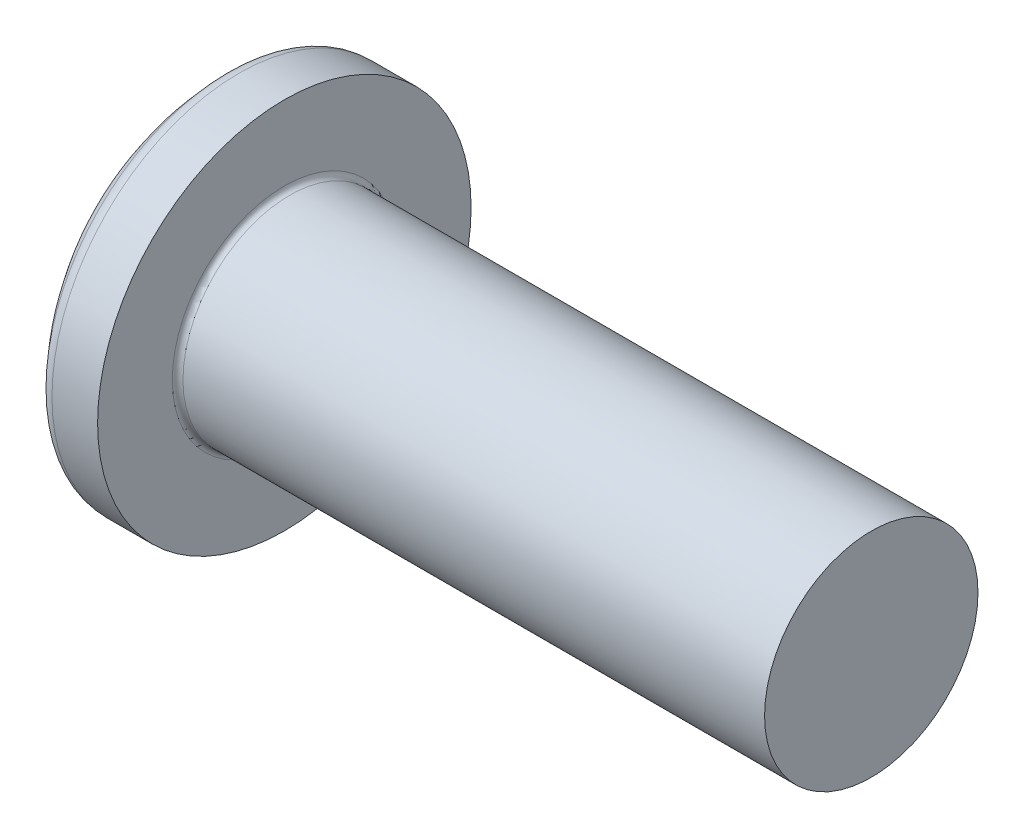
SolidWorks part; units mm, degrees
ref_plane "Plane1" through (0, 0, 0) normal (0, 0, 1) x (1, 0, 0)
ref_plane "Plane2" through (0, 0, 0) normal (0, 1, 0) x (1, 0, 0)
ref_plane "Plane3" through (0, 0, 0) normal (1, 0, 0) x (0, 0, -1)
sketch "BodySke" plane through (0, 0, 0) normal (0, 0, 1) x (1, 0, 0)
  line L0 (2.4, 2) -> (2.4, 3.5)
  line L1 (2.65, 6.35) -> (2.65, -3.175) construction
  line L2 (-25.4, 0) -> (127, 0) construction
  line L3 (13.4, 0) -> (0, 0)
  line L4 (2.4, 2) -> (13.4, 2)
  line L5 (13.4, 2) -> (13.4, 0)
  line L6 (1.5446, 3.5) -> (2.4, 3.5)
  line L8 (7.4, 6.35) -> (7.4, -3.175) construction
  arc A0 (1.3473, 3.4144) -> (0, 0) centre (5, 0) ccw
  arc A2 (1.3473, 3.4144) -> (1.5446, 3.5) centre (1.5446, 3.23) cw
  dimension "Head_crown_rad" = 5
  dimension "Head_fillet_rad" = 0.27
  dimension "Length" = 11
  dimension "Head_ht" = 2.4
  dimension "Head_dia" = 7
  dimension "Advance" = 0.5
  dimension "Thread_nom" = 6
  dimension "Diameter" = 4
revolve "Base-Revolve" add sketch "BodySke"
cosmetic thread "ThreadCosmetic" [suppressed]
fillet "Fillet1" radius 0.1 1 edges at (2.4, 0, 2)
sketch "Sketch3" plane through (0, 0, 0) normal (1, 0, 0) x (0, 0, -1)
  line L0 (0.37, -1.4) -> (-0.37, -1.4)
  line L1 (0.37, -1.4) -> (0.37, 1.4)
  line L2 (-0.37, 1.4) -> (0.37, 1.4)
  line L3 (-0.37, 1.4) -> (-0.37, -1.4)
  dimension "Cross_dia" = 2.8
  dimension "D1" = 1.4
  dimension "Cross_width" = 0.74
  dimension "D2" = 0.37
ref_plane "Plane4" through (1.75, 0, 0) normal (1, 0, 0) x (0, 0, -1)
sketch "Sketch4" plane through (1.75, 0, 0) normal (1, 0, 0) x (0, 0, -1)
  line L0 (0.37, -0.5275) -> (-0.37, -0.5275)
  line L1 (0.37, -0.5275) -> (0.37, 0.5275)
  line L2 (-0.37, 0.5275) -> (0.37, 0.5275)
  line L3 (-0.37, 0.5275) -> (-0.37, -0.5275)
  dimension "D1" = 0.74
  dimension "D2" = 1.055
  dimension "D3" = 0.37
  dimension "D4" = 0.5275
loft "Recess" cut profiles "Sketch3", "Sketch4"
pattern_circular "RecPat" count 2 every 90 about axis through (0, 0, 0) along (1, 0, 0) of "Recess"
sketch "RecCorSke" plane through (0, 0, 0) normal (0, 0, 1) x (1, 0, 0)
  line L0 (-3.175, 0) -> (15.875, 0) construction
  line L1 (-25.4, 0) -> (127, 0) construction
  line L2 (0, 0) -> (0, 0.6784)
  line L3 (0, 0.6784) -> (1.75, 0.556)
  line L4 (1.75, 0.556) -> (1.9307, 0)
  line L5 (1.9307, 0) -> (0, 0)
  dimension "Diameter" = 1.112
  dimension "Depth" = 1.75
  dimension "Draft_angle" = 4
  dimension "Bottom_angle" = 18
revolve "RecessCore" cut sketch "RecCorSke" angle 360 about L0
sketch "ThdSchSke" plane through (0, 0, 0) normal (0, 0, 1) x (1, 0, 0)
  line L0 (7.4, -1.2195) -> (6.8535, -2)
  line L1 (7.4, -1.2195) -> (7.9465, -2)
  line L2 (7.9465, -2) -> (7.9465, -2.5)
  line L3 (-3.175, 0) -> (5.1513, 0) construction
  line L5 (7.9465, -2.5) -> (6.8535, -2.5)
  line L6 (6.8535, -2.5) -> (6.8535, -2)
  dimension "Diameter" = 4
  dimension "SideAngle" = 55
  dimension "VeeAngle" = 70
  dimension "Thread_minor" = 2.439
  dimension "Overcut" = 5
  dimension "Start" = 7.4
revolve "ThreadSchematic" [suppressed] cut sketch "ThdSchSke" angle 360 about L3
pattern_linear "ThdSchPat" [suppressed]
equation "\"D1@Sketch3\" = \"Cross_dia@Sketch3\" / 2"
equation "\"D2@Sketch3\" = \"Cross_width@Sketch3\" / 2"
equation "\"Depth@RecCorSke\" = \"Cross_depth@Plane4\""
equation "\"D1@Sketch4\" = \"Cross_width@Sketch3\""
equation "\"D2@Sketch4\" = \"Cross_dia@Sketch3\" - 2.0 * \"Cross_depth@Plane4\" * tan(26.5  * 0.017453292)"
equation "\"D3@Sketch4\" = \"D1@Sketch4\" / 2"
equation "\"D4@Sketch4\" = \"D2@Sketch4\" / 2"
equation "\"Thread_length@ThreadCosmetic\" = ((sgn( (\"Length@BodySke\" - \"Advance@BodySke\" * 2.0 ) - \"Thread_nom@BodySke\" )-1)*( (\"Length@BodySke\" - \"Advance@BodySke\" * 2.0 ) - \"Thread_nom@BodySke\" ))/-2+ \"Thread_nom@BodySke\""
equation "\"Thread_minor@ThdSchSke\" = \"Thread_minor@ThreadCosmetic\""
equation "\"Diameter@ThdSchSke\" = \"Diameter@BodySke\""
equation "\"Overcut@ThdSchSke\" = \"Diameter@BodySke\" * 1.25"
equation "\"Start@ThdSchSke\" = \"Head_ht@BodySke\" + \"Length@BodySke\" - \"Thread_length@ThreadCosmetic\"  '---Non-countersunk---"
equation "\"Num_threads@ThdSchPat\" = int( \"Thread_length@ThreadCosmetic\" / \"Advance@BodySke\" + 0.999 )  + 1"
equation "\"Advance@ThdSchPat\" = \"Thread_length@ThreadCosmetic\" /  (\"Num_threads@ThdSchPat\" - 1) 'relax it"
